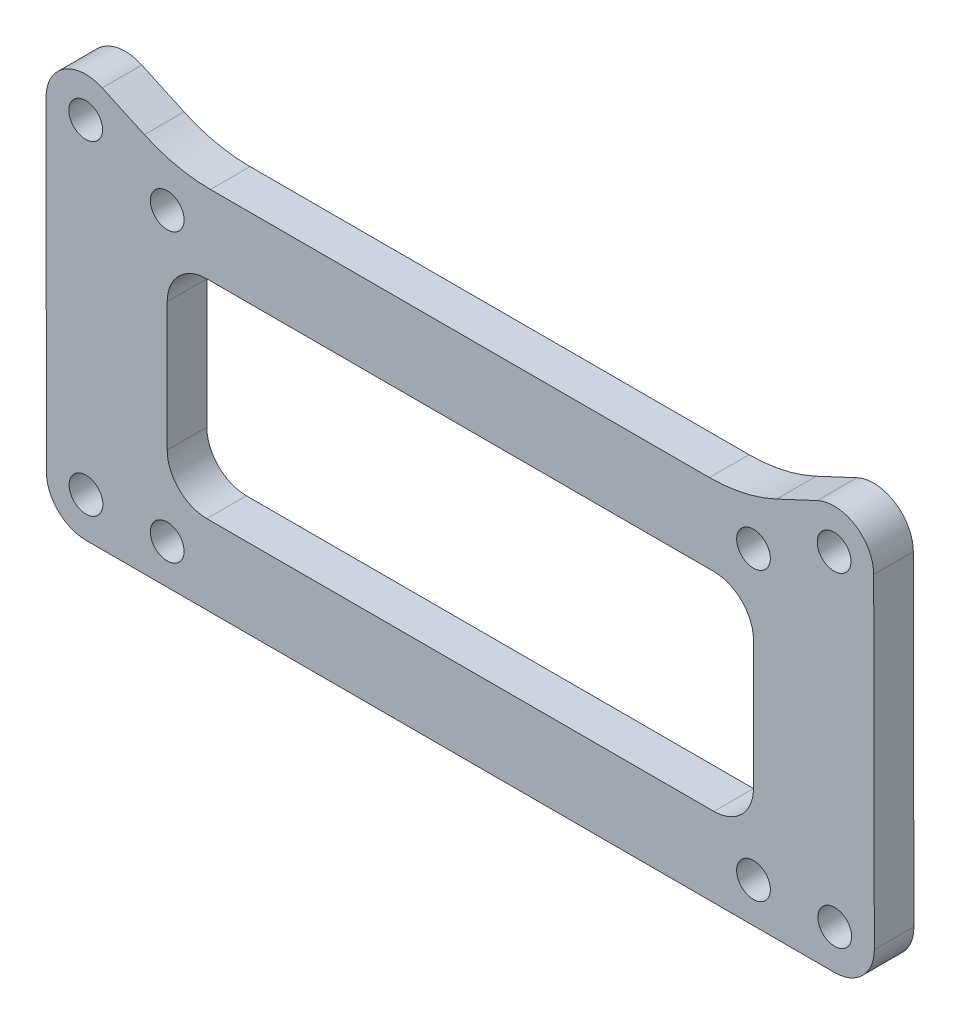
SolidWorks part; units mm, degrees
material "ABS PC"
ref_plane "Front Plane" through (0, 0, 0) normal (0, 0, 1) x (1, 0, 0)
ref_plane "Top Plane" through (0, 0, 0) normal (0, 1, 0) x (1, 0, 0)
ref_plane "Right Plane" through (0, 0, 0) normal (1, 0, 0) x (0, 0, -1)
sketch "Sketch2" plane through (0, 0, 0) normal (0, 0, 1) x (1, 0, 0)
  line L0 (0, -3.175) -> (60.025, -3.175)
  line L1 (6.5125, 0) -> (53.5125, 0) construction
  line L4 (0, -3.175) -> (6.5125, -3.175)
  line L5 (53.5125, -3.175) -> (60.025, -3.175)
  line L6 (-3.175, 0) -> (-3.2, 26)
  line L7 (63.15, 26.025) -> (63.2, 0.0061)
  line L8 (1.2992, 28.8857) -> (7.8367, 25.8857)
  line L9 (58.629, 28.9006) -> (52.1665, 25.8756)
  line L10 (6.5125, 26.175) -> (53.5125, 26.175)
  line L11 (30.0125, 26.175) -> (30.0125, -3.175) construction
  line L12 (53.5125, 3.175) -> (6.5125, 3.175)
  line L13 (53.5125, 3.175) -> (53.5125, 19.825)
  line L14 (53.5125, 19.825) -> (6.5125, 19.825)
  line L15 (6.5125, 3.175) -> (6.5125, 19.825)
  line L16 (53.5125, 3.175) -> (6.5125, 19.825) construction
  line L17 (53.5125, 19.825) -> (6.5125, 3.175) construction
  circle A0 centre (0, 0) radius 3.175
  circle A1 centre (60.025, 0) radius 3.175
  circle A2 centre (-0.025, 26) radius 3.175
  circle A3 centre (59.975, 26.025) radius 3.175
  circle A6 centre (6.5125, 0) radius 3.175
  circle A7 centre (53.5125, 0) radius 3.175
  circle A8 centre (53.5125, 23) radius 3.175
  circle A9 centre (6.5125, 23) radius 3.175
  point P21 (30.0125, 11.5)
  point P24 (30.0125, 0)
  circle M15 centre (0, 0) radius 1.143
  arc M16 (-1.1906, 2.0622) -> (-2.3813, 0) centre (0, 0) ccw
  arc M17 (-2.3813, 0) -> (-1.1906, -2.0622) centre (0, 0) ccw
  arc M18 (-1.1906, -2.0622) -> (1.1906, -2.0622) centre (0, 0) ccw
  arc M19 (1.1906, -2.0622) -> (2.3813, 0) centre (0, 0) ccw
  arc M20 (2.3813, 0) -> (1.1906, 2.0622) centre (0, 0) ccw
  arc M21 (1.1906, 2.0622) -> (-1.1906, 2.0622) centre (0, 0) ccw
  dimension "D1" = 6.35
  dimension "D2" = 6.35
  dimension "D3" = 47
  dimension "D4" = 23
extrude "Boss-Extrude1" add sketch "Sketch2" along normal blind 3.175 contours A6 A0 M16 M21 M20 M19 M18 M17 | A6 A0 | A7 A1 | A1 A7 | A1 A7 | A0 A6 | M21 M16 M17 M18 M19 M20 M15 | M15 | A9 L10 L8 A2 L6 A0 A6 L15 | A7 L12 A6 L0 | A8 L13 A7 A1 L7 A3 L9 L10 | A7 L0 A1 | A6 A0 L0 | A3 | A9 L14 A8 L9 L10 L8 | A9 | A2 | A9 L8 L10 | A8 | A8 L10 L9
fillet "Fillet1" radius 3.175 4 edges at (6.5125, 3.175, 1.5875) (53.5125, 3.175, 1.5875) (53.5125, 19.825, 1.5875) (6.5125, 19.825, 1.5875)
fillet "Fillet2" radius 12.7 2 edges at (52.8062, 26.175, 1.5875) (7.2062, 26.175, 1.5875)
hole_wizard "#2 Clearance Hole1" positions "Sketch3" profile "Sketch4" hole size "#2" standard "ANSI Inch" end condition through all
sketch "Sketch3" plane through (0, 0, 3.175) normal (0, 0, 1) x (1, 0, 0)
  point P0 (6.5125, 23)
  point P3 (53.5125, 23)
  point P6 (53.5125, 0)
  point P9 (6.5125, 0)
sketch "Sketch4" plane through (6.5125, 23, 3.175) normal (1, 0, 0) x (0, -1, 0)
  line L0 (0, 0) -> (0, 3.175)
  line L1 (0, 3.175) -> (1.3525, 3.175)
  line L2 (1.3525, 3.175) -> (1.3525, 0)
  line L5 (1.3525, 0) -> (0, 0)
  line L11 (0, -6.35) -> (0, 107.95) construction
  dimension "Thru Hole Dia." = 2.7051
  dimension "Thru Hole Depth" = 3.175
hole_wizard "#2 Clearance Hole2" positions "Sketch5" profile "Sketch6" hole size "#2" standard "ANSI Inch" end condition through all
sketch "Sketch5" plane through (0, 0, 3.175) normal (0, 0, 1) x (1, 0, 0)
  point P0 (-0.025, 26)
  point P3 (0, 0)
  point P6 (60.025, 0)
  point P9 (59.975, 26.025)
sketch "Sketch6" plane through (-0.025, 26, 3.175) normal (1, 0, 0) x (0, -1, 0)
  line L0 (0, 0) -> (0, 3.175)
  line L1 (0, 3.175) -> (1.3525, 3.175)
  line L2 (1.3525, 3.175) -> (1.3525, 0)
  line L5 (1.3525, 0) -> (0, 0)
  line L11 (0, -6.35) -> (0, 107.95) construction
  dimension "Thru Hole Dia." = 2.7051
  dimension "Thru Hole Depth" = 3.175
